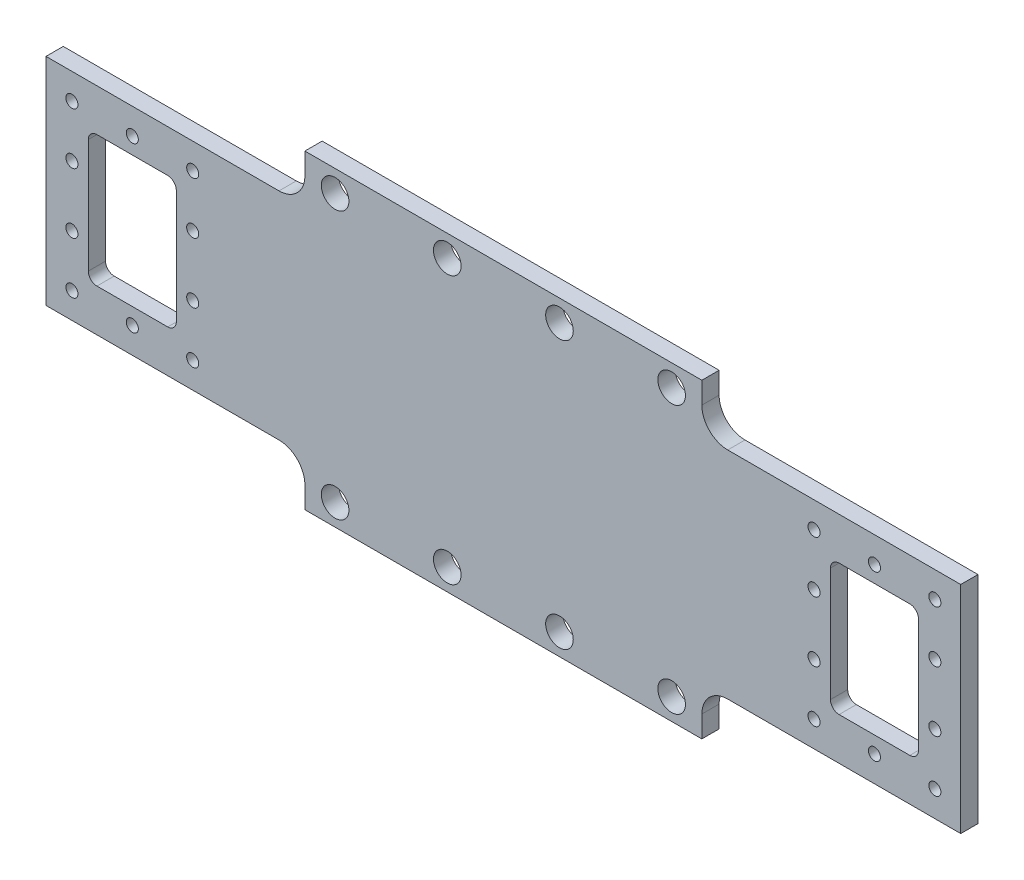
SolidWorks part; units mm, degrees
ref_plane "前视基准面" through (0, 0, 0) normal (0, 0, 1) x (1, 0, 0)
ref_plane "上视基准面" through (0, 0, 0) normal (0, 1, 0) x (1, 0, 0)
ref_plane "右视基准面" through (0, 0, 0) normal (1, 0, 0) x (0, 0, -1)
sketch "草图1" plane through (0, 0, 0) normal (0, 0, 1) x (1, 0, 0)
  line L1 (-530, 180) -> (530, 180)
  line L2 (-530, 180) -> (-530, -180)
  line L3 (-530, -180) -> (530, -180)
  line L4 (530, 180) -> (530, -180)
  line L5 (-530, 180) -> (530, -180) construction
  line L6 (-530, -180) -> (530, 180) construction
  point P0 (0, 0)
  dimension "D1" = 1060
  dimension "D2" = 360
extrude "凸台-拉伸1" add sketch "草图1" against normal blind 20
sketch "草图2" plane through (0, 0, 0) normal (0, 0, 1) x (1, 0, 0)
  line L0 (0, 0) -> (0, 278.5805) construction
  line L1 (-530, 180) -> (-230, 180)
  line L2 (-530, 180) -> (-530, 125)
  line L3 (-530, 125) -> (-260, 125)
  line L4 (-230, 180) -> (-230, 155)
  line L5 (0, 0) -> (-432.7043, 0) construction
  line L6 (230, 180) -> (230, 155)
  line L7 (530, 125) -> (260, 125)
  line L8 (530, 180) -> (530, 125)
  line L9 (530, 180) -> (230, 180)
  line L10 (530, -180) -> (230, -180)
  line L11 (530, -180) -> (530, -125)
  line L12 (530, -125) -> (260, -125)
  line L13 (230, -180) -> (230, -155)
  line L14 (-230, -180) -> (-230, -155)
  line L15 (-530, -125) -> (-260, -125)
  line L16 (-530, -180) -> (-530, -125)
  line L17 (-530, -180) -> (-230, -180)
  arc A0 (260, -125) -> (230, -155) centre (260, -155) ccw
  arc A1 (230, 155) -> (260, 125) centre (260, 155) ccw
  arc A2 (-230, -155) -> (-260, -125) centre (-260, -155) ccw
  arc A3 (-260, 125) -> (-230, 155) centre (-260, 155) ccw
  point P23 (230, -125)
  point P26 (230, 125)
  point P29 (-230, -125)
  point P32 (-230, 125)
  dimension "D3" = 30
  dimension "D1" = 55
  dimension "D2" = 300
extrude "切除-拉伸1" cut sketch "草图2" against normal up to next
sketch "草图3" plane through (0, 0, 0) normal (0, 0, 1) x (1, 0, 0)
  line L0 (0, 0) -> (347.3211, 0) construction
  line L2 (-230, 155) -> (-230, 180) construction
  line L3 (0, 0) -> (0, 119.0435) construction
  line L4 (-471, 76) -> (-389, 76)
  line L5 (-481, 66) -> (-481, -66)
  line L6 (-471, -76) -> (-389, -76)
  line L7 (-379, 66) -> (-379, -66)
  line L8 (-530, 125) -> (-530, -125) construction
  line L9 (-260, -125) -> (-530, -125) construction
  line L10 (-530, 125) -> (-260, 125) construction
  line L11 (379, 66) -> (379, -66)
  line L12 (471, -76) -> (389, -76)
  line L13 (481, 66) -> (481, -66)
  line L14 (471, 76) -> (389, 76)
  circle A0 centre (-195, 155) radius 16
  circle A1 centre (-65, 155) radius 16
  circle A2 centre (65, 155) radius 16
  circle A3 centre (195, 155) radius 16
  circle A4 centre (195, -155) radius 16
  circle A5 centre (65, -155) radius 16
  circle A6 centre (-65, -155) radius 16
  circle A7 centre (-195, -155) radius 16
  arc A8 (-481, -66) -> (-471, -76) centre (-471, -66) ccw
  arc A9 (-389, -76) -> (-379, -66) centre (-389, -66) ccw
  arc A10 (-389, 76) -> (-379, 66) centre (-389, 66) cw
  arc A11 (-471, 76) -> (-481, 66) centre (-471, 66) ccw
  circle A12 centre (-500, 95) radius 7
  circle A13 centre (-430, 95) radius 7
  circle A14 centre (-360, 95) radius 7
  circle A15 centre (-500, 35) radius 7
  circle A16 centre (-500, -35) radius 7
  circle A17 centre (-500, -95) radius 7
  circle A18 centre (-360, 35) radius 7
  circle A19 centre (-360, -35) radius 7
  circle A20 centre (-360, -95) radius 7
  circle A21 centre (-430, -95) radius 7
  circle A22 centre (430, -95) radius 7
  circle A23 centre (360, -95) radius 7
  circle A24 centre (360, -35) radius 7
  circle A25 centre (360, 35) radius 7
  circle A26 centre (500, -95) radius 7
  circle A27 centre (500, -35) radius 7
  circle A28 centre (500, 35) radius 7
  circle A29 centre (360, 95) radius 7
  circle A30 centre (430, 95) radius 7
  circle A31 centre (500, 95) radius 7
  arc A32 (471, 76) -> (481, 66) centre (471, 66) cw
  arc A33 (389, 76) -> (379, 66) centre (389, 66) ccw
  arc A34 (389, -76) -> (379, -66) centre (389, -66) cw
  arc A35 (481, -66) -> (471, -76) centre (471, -66) cw
  point P32 (-481, -76)
  point P35 (-379, -76)
  point P38 (-379, 76)
  point P61 (0, 0)
  point P62 (0, 0)
  point P63 (0, 0)
  point P64 (0, 0)
  point P65 (0, 0)
  point P66 (-505.9258, -95.6228)
  point P67 (0, 0)
  point P68 (0, 0)
  point P103 (379, 76)
  point P104 (379, -76)
  point P105 (481, -76)
  dimension "D1" = 310
  dimension "D2" = 130
  dimension "D3" = 130
  dimension "D4" = 130
  dimension "D5" = 35
  dimension "D6" = 32
  dimension "D7" = 32
  dimension "D8" = 32
  dimension "D9" = 32
  dimension "D14" = 10
  dimension "D15" = 30
  dimension "D16" = 70
  dimension "D17" = 70
  dimension "D18" = 30
  dimension "D19" = 60
  dimension "D20" = 70
  dimension "D21" = 60
  dimension "D22" = 14
  dimension "D23" = 14
  dimension "D24" = 14
  dimension "D25" = 14
  dimension "D26" = 14
  dimension "D27" = 14
  dimension "D28" = 14
  dimension "D29" = 14
  dimension "D30" = 14
  dimension "D31" = 14
  dimension "D10" = 102
  dimension "D11" = 49
  dimension "D12" = 152
  dimension "D13" = 49
extrude "切除-拉伸2" cut sketch "草图3" against normal up to next (20 mm away)
